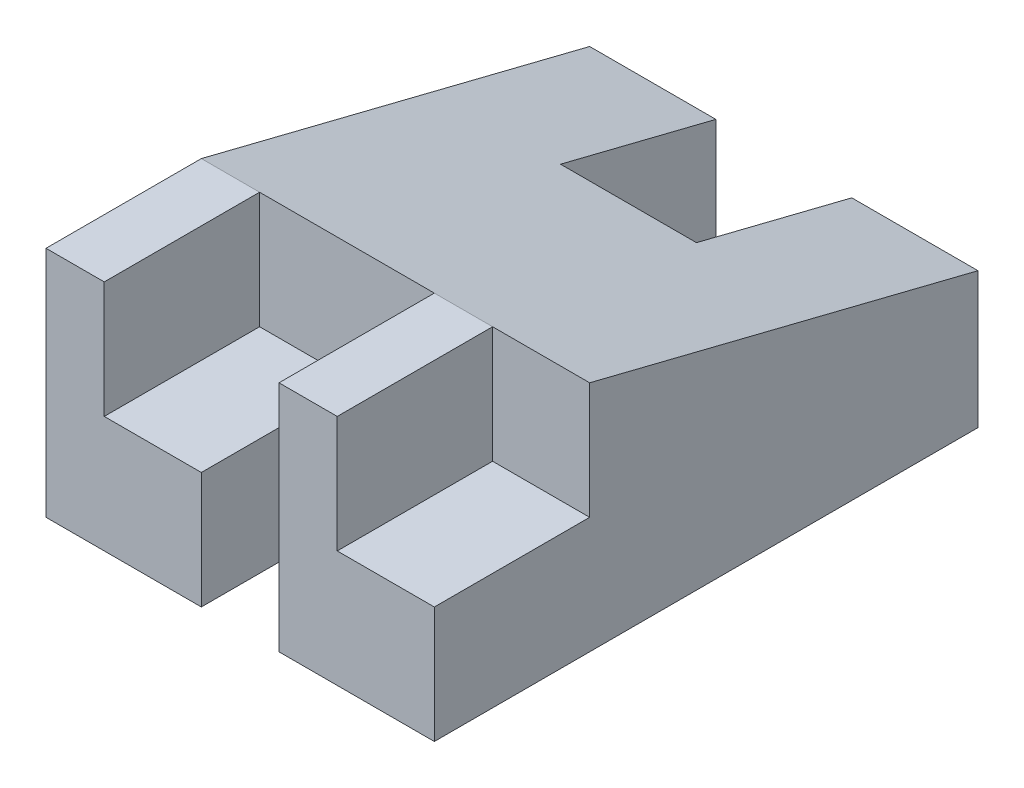
SolidWorks part; units mm, degrees
ref_plane "Front Plane" through (0, 0, 0) normal (0, 0, 1) x (1, 0, 0)
ref_plane "Top Plane" through (0, 0, 0) normal (0, 1, 0) x (1, 0, 0)
ref_plane "Right Plane" through (0, 0, 0) normal (1, 0, 0) x (0, 0, -1)
sketch "Sketch1" plane through (0, 0, 0) normal (1, 0, 0) x (0, 0, -1)
  line L4 (-31.75, 0) -> (31.75, 0)
  line L5 (31.75, 0) -> (31.75, 22.225)
  line L6 (31.75, 22.225) -> (-31.75, 38.1)
  line L7 (-31.75, 38.1) -> (-31.75, 0)
  dimension "D1" = 22.225
  dimension "D2" = 63.5
  dimension "D3" = 38.1
extrude "Boss-Extrude1" add sketch "Sketch1" against normal blind 63.5
sketch "Sketch5" plane through (0, 0, 0) normal (0, -1, 0) x (1, 0, 0)
  line L0 (-63.5, -31.75) -> (-42.8625, -31.75)
  line L1 (-63.5, -31.75) -> (0, -31.75) construction
  line L2 (-42.8625, -31.75) -> (-42.8625, -6.35)
  line L3 (-42.8625, -6.35) -> (-20.6375, -6.35)
  line L4 (-20.6375, -6.35) -> (-20.6375, -31.75)
  line L5 (-20.6375, -31.75) -> (0, -31.75)
  line M8 (-63.5, -31.75) -> (0, -31.75)
  dimension "D1" = 20.6375
  dimension "D2" = 25.4
extrude "Cut-Extrude1" cut sketch "Sketch5" against normal blind 63.5 and the other way through all contours L4 L3 L2 M8
sketch "Sketch9" plane through (0, 0, 31.75) normal (0, 0, 1) x (1, 0, 0)
  line L0 (0, 0) -> (-25.4, 0)
  line L1 (-63.5, 0) -> (0, 0) construction
  line L2 (-25.4, 0) -> (-25.4, 38.1)
  line L3 (-63.5, 38.1) -> (0, 38.1) construction
  line L4 (-25.4, 38.1) -> (-15.875, 38.1)
  line L5 (-15.875, 38.1) -> (-15.875, 19.05)
  line L6 (-15.875, 19.05) -> (0, 19.05)
  line L7 (0, 38.1) -> (0, 0) construction
  line L8 (0, 19.05) -> (0, 0)
  line L9 (-38.1, 0) -> (-63.5, 0)
  line L10 (-63.5, 0) -> (-63.5, 38.1)
  line L11 (-63.5, 38.1) -> (-53.975, 38.1)
  line L12 (-53.975, 38.1) -> (-53.975, 19.05)
  line L13 (-53.975, 19.05) -> (-38.1, 19.05)
  line L14 (-38.1, 19.05) -> (-38.1, 0)
  line L15 (-63.5, 38.1) -> (-63.5, 0) construction
  point P10 (-92.1902, 0)
  dimension "D1" = 25.4
  dimension "D2" = 15.875
  dimension "D3" = 2
extrude "Boss-Extrude2" add sketch "Sketch9" along normal blind 25.4
